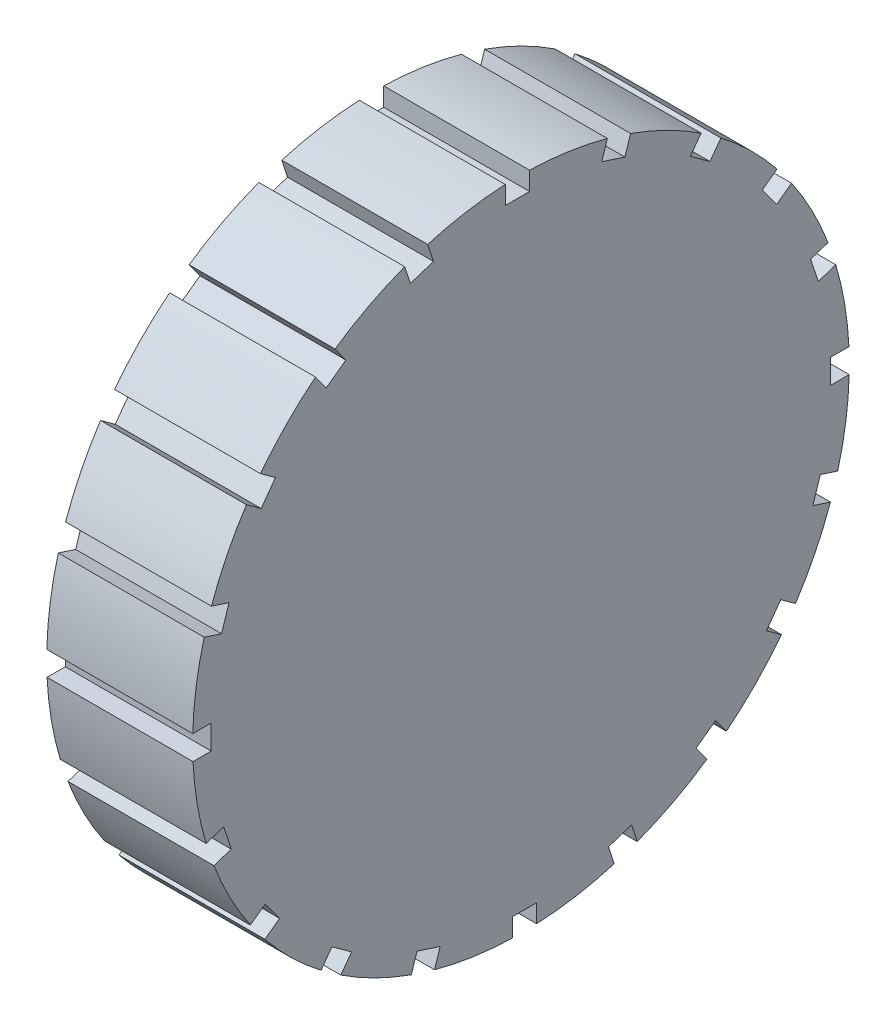
SolidWorks part; units mm, degrees
ref_plane "Front Plane" through (0, 0, 0) normal (0, 0, 1) x (1, 0, 0)
ref_plane "Top Plane" through (0, 0, 0) normal (0, 1, 0) x (1, 0, 0)
ref_plane "Right Plane" through (0, 0, 0) normal (1, 0, 0) x (0, 0, -1)
sketch "Sketch2" plane through (0, 0, 0) normal (0, 0, 1) x (1, 0, 0)
  line L0 (6, 0) -> (-6, 0)
  line L1 (-6, 0) -> (-6, 1.5)
  line L2 (-6, 1.5) -> (6, 1.5)
  line L3 (6, 1.5) -> (6, 0)
  line L4 (6, 0) -> (6, 27)
  line L5 (6, 27) -> (18, 27)
  line L6 (18, 27) -> (18, 0)
  line L7 (18, 0) -> (6, 0)
  dimension "D1" = 12
  dimension "D2" = 1.5
  dimension "D3" = 27
  dimension "D4" = 12
revolve "Revolve1" add sketch "Sketch2" angle 360 about L0
sketch "Sketch3" plane through (18, 0, 0) normal (1, 0, 0) x (0, 0, -1)
  line L76 (-7.1945, 24.4423) -> (-8.7426, 29.2066)
  line L77 (-9.0966, 23.8242) -> (-7.1945, 24.4423)
  line L78 (-10.6417, 28.5795) -> (-9.0966, 23.8242)
  line L79 (-8.7426, 29.2066) -> (-10.6417, 28.5795)
  line L80 (0.7107, 25.4692) -> (0.7107, 30.4788)
  line L81 (0.7107, 30.4788) -> (-1.2893, 30.4692)
  line L82 (-1.2893, 30.4692) -> (-1.2893, 25.4692)
  line L83 (-1.2893, 25.4692) -> (0.7107, 25.4692)
  line L84 (8.5463, 24.003) -> (10.0943, 28.7674)
  line L85 (10.0943, 28.7674) -> (8.1893, 29.3763)
  line L86 (8.1893, 29.3763) -> (6.6442, 24.6211)
  line L87 (6.6442, 24.6211) -> (8.5463, 24.003)
  line L88 (15.5454, 20.1873) -> (18.4899, 24.2401)
  line L89 (18.4899, 24.2401) -> (16.8663, 25.4079)
  line L90 (16.8663, 25.4079) -> (13.9273, 21.3629)
  line L91 (13.9273, 21.3629) -> (15.5454, 20.1873)
  line L92 (21.0227, 14.3955) -> (25.0756, 17.34)
  line L93 (25.0756, 17.34) -> (23.8923, 18.9524)
  line L94 (23.8923, 18.9524) -> (19.8472, 16.0135)
  line L95 (19.8472, 16.0135) -> (21.0227, 14.3955)
  line L96 (24.4423, 7.1945) -> (29.2066, 8.7426)
  line L97 (29.2066, 8.7426) -> (28.5795, 10.6417)
  line L98 (28.5795, 10.6417) -> (23.8242, 9.0966)
  line L99 (23.8242, 9.0966) -> (24.4423, 7.1945)
  line L100 (25.4692, -0.7107) -> (30.4788, -0.7107)
  line L101 (30.4788, -0.7107) -> (30.4692, 1.2893)
  line L102 (30.4692, 1.2893) -> (25.4692, 1.2893)
  line L103 (25.4692, 1.2893) -> (25.4692, -0.7107)
  line L104 (24.003, -8.5463) -> (28.7674, -10.0943)
  line L105 (28.7674, -10.0943) -> (29.3763, -8.1893)
  line L106 (29.3763, -8.1893) -> (24.6211, -6.6442)
  line L107 (24.6211, -6.6442) -> (24.003, -8.5463)
  line L108 (20.1873, -15.5454) -> (24.2401, -18.4899)
  line L109 (24.2401, -18.4899) -> (25.4079, -16.8663)
  line L110 (25.4079, -16.8663) -> (21.3629, -13.9273)
  line L111 (21.3629, -13.9273) -> (20.1873, -15.5454)
  line L112 (14.3955, -21.0227) -> (17.34, -25.0756)
  line L113 (17.34, -25.0756) -> (18.9524, -23.8923)
  line L114 (18.9524, -23.8923) -> (16.0135, -19.8472)
  line L115 (16.0135, -19.8472) -> (14.3955, -21.0227)
  line L116 (7.1945, -24.4423) -> (8.7426, -29.2066)
  line L117 (8.7426, -29.2066) -> (10.6417, -28.5795)
  line L118 (10.6417, -28.5795) -> (9.0966, -23.8242)
  line L119 (9.0966, -23.8242) -> (7.1945, -24.4423)
  line L120 (-0.7107, -25.4692) -> (-0.7107, -30.4788)
  line L121 (-0.7107, -30.4788) -> (1.2893, -30.4692)
  line L122 (1.2893, -30.4692) -> (1.2893, -25.4692)
  line L123 (1.2893, -25.4692) -> (-0.7107, -25.4692)
  line L124 (-8.5463, -24.003) -> (-10.0943, -28.7674)
  line L125 (-10.0943, -28.7674) -> (-8.1893, -29.3763)
  line L126 (-8.1893, -29.3763) -> (-6.6442, -24.6211)
  line L127 (-6.6442, -24.6211) -> (-8.5463, -24.003)
  line L128 (-15.5454, -20.1873) -> (-18.4899, -24.2401)
  line L129 (-18.4899, -24.2401) -> (-16.8663, -25.4079)
  line L130 (-16.8663, -25.4079) -> (-13.9273, -21.3629)
  line L131 (-13.9273, -21.3629) -> (-15.5454, -20.1873)
  line L132 (-21.0227, -14.3955) -> (-25.0756, -17.34)
  line L133 (-25.0756, -17.34) -> (-23.8923, -18.9524)
  line L134 (-23.8923, -18.9524) -> (-19.8472, -16.0135)
  line L135 (-19.8472, -16.0135) -> (-21.0227, -14.3955)
  line L136 (-24.4423, -7.1945) -> (-29.2066, -8.7426)
  line L137 (-29.2066, -8.7426) -> (-28.5795, -10.6417)
  line L138 (-28.5795, -10.6417) -> (-23.8242, -9.0966)
  line L139 (-23.8242, -9.0966) -> (-24.4423, -7.1945)
  line L140 (-25.4692, 0.7107) -> (-30.4788, 0.7107)
  line L141 (-30.4788, 0.7107) -> (-30.4692, -1.2893)
  line L142 (-30.4692, -1.2893) -> (-25.4692, -1.2893)
  line L143 (-25.4692, -1.2893) -> (-25.4692, 0.7107)
  line L144 (-24.003, 8.5463) -> (-28.7674, 10.0943)
  line L145 (-28.7674, 10.0943) -> (-29.3763, 8.1893)
  line L146 (-29.3763, 8.1893) -> (-24.6211, 6.6442)
  line L147 (-24.6211, 6.6442) -> (-24.003, 8.5463)
  line L148 (-20.1873, 15.5454) -> (-24.2401, 18.4899)
  line L149 (-24.2401, 18.4899) -> (-25.4079, 16.8663)
  line L150 (-25.4079, 16.8663) -> (-21.3629, 13.9273)
  line L151 (-21.3629, 13.9273) -> (-20.1873, 15.5454)
  line L152 (-14.3955, 21.0227) -> (-17.34, 25.0756)
  line L153 (-17.34, 25.0756) -> (-18.9524, 23.8923)
  line L154 (-18.9524, 23.8923) -> (-16.0135, 19.8472)
  line L155 (-16.0135, 19.8472) -> (-14.3955, 21.0227)
  point P83 (0, 0)
  dimension "D2" = 5
  dimension "D3" = 2
  dimension "D4" = 2
  dimension "D1" = 20
extrude "Cut-Extrude3" cut sketch "Sketch3" against normal up to surface (12 mm away) up to face at (6, 0, -27)
